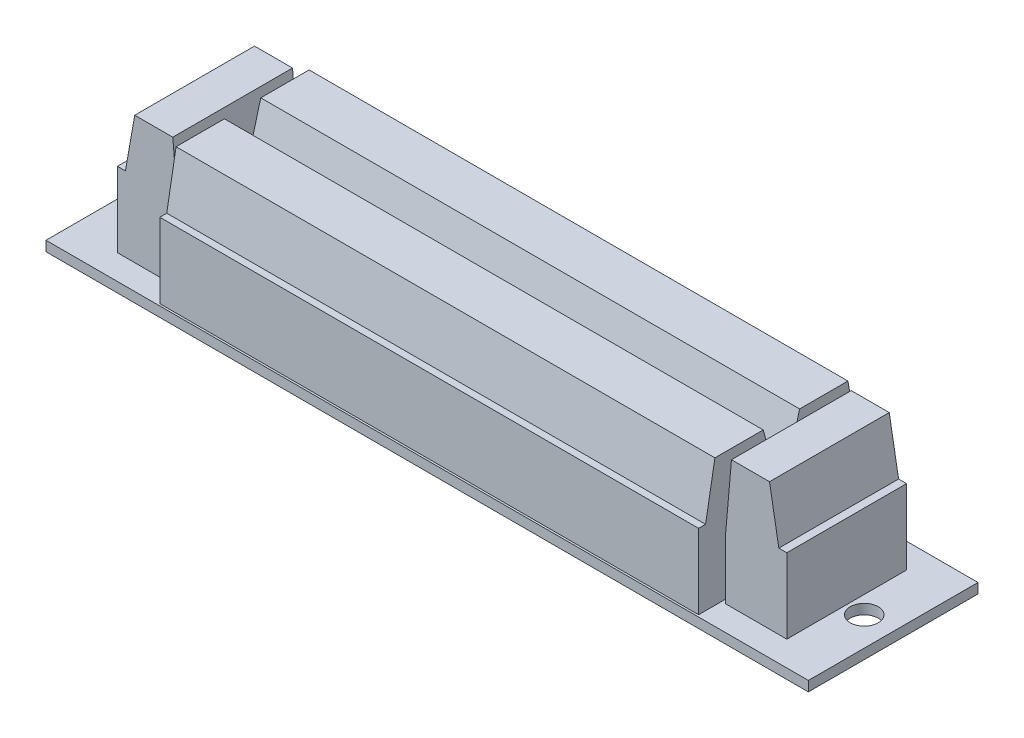
SolidWorks part; units mm, degrees
ref_plane "Front Plane" through (0, 0, 0) normal (0, 0, 1) x (1, 0, 0)
ref_plane "Top Plane" through (0, 0, 0) normal (0, 1, 0) x (1, 0, 0)
ref_plane "Right Plane" through (0, 0, 0) normal (1, 0, 0) x (0, 0, -1)
sketch "Sketch1" plane through (0, 0, 0) normal (0, 1, 0) x (1, 0, 0)
  line L0 (0, 10.795) -> (0, -10.795) construction
  line L1 (-48.514, 10.795) -> (48.514, 10.795)
  line L2 (-48.514, 10.795) -> (-48.514, -10.795)
  line L3 (-48.514, -10.795) -> (48.514, -10.795)
  line L4 (48.514, 10.795) -> (48.514, -10.795)
  line L5 (-48.514, 10.795) -> (48.514, -10.795) construction
  line L6 (-48.514, -10.795) -> (48.514, 10.795) construction
  circle A0 centre (-44.831, 0) radius 1.778
  circle A1 centre (44.831, 0) radius 1.778
  point P0 (0, 0)
  dimension "D3" = 3.556
  dimension "D1" = 97.028
  dimension "D2" = 21.59
  dimension "D4" = 89.662
extrude "Boss-Extrude1" add sketch "Sketch1" along normal mid plane 1.27
sketch "Sketch2" plane through (0, 0, 0) normal (1, 0, 0) x (0, 0, -1)
  line L0 (-10.541, 0.635) -> (-10.541, 10.16)
  line L1 (-10.541, 10.16) -> (-9.652, 10.16)
  line L2 (-9.652, 10.16) -> (-8.4651, 16.891)
  line L3 (-8.4651, 16.891) -> (-2.314, 16.891)
  line L4 (-2.314, 16.891) -> (0, 8.255)
  line L5 (0, 8.255) -> (0, 0.635) construction
  line L6 (-10.795, 0.635) -> (10.795, 0.635) construction
  line L7 (10.541, 0.635) -> (-10.541, 0.635)
  line L8 (10.541, 0.635) -> (10.541, 10.16)
  line L9 (10.541, 10.16) -> (9.652, 10.16)
  line L10 (9.652, 10.16) -> (8.4651, 16.891)
  line L11 (8.4651, 16.891) -> (2.314, 16.891)
  line L12 (2.314, 16.891) -> (0, 8.255)
  point P10 (-10.0965, 10.16)
  point P14 (10.0965, 10.16)
  dimension "D1" = 9.525
  dimension "D2" = 0.889
  dimension "D3" = 16.256
  dimension "D4" = 100
  dimension "D5" = 7.62
  dimension "D6" = 30
  dimension "D7" = 0.254
extrude "Boss-Extrude2" add sketch "Sketch2" along normal mid plane 68.58
sketch "Sketch3" plane through (0, 0, 0) normal (0, 0, 1) x (1, 0, 0)
  line L0 (-34.798, 0.635) -> (-34.798, 8.255)
  line L1 (-48.514, 0.635) -> (48.514, 0.635) construction
  line L2 (-34.798, 8.255) -> (-35.5536, 16.891)
  line L3 (-35.5536, 16.891) -> (-40.3936, 16.891)
  line L4 (-40.3936, 16.891) -> (-41.5804, 10.16)
  line L5 (-41.5804, 10.16) -> (-42.5964, 10.16)
  line L6 (-42.5964, 10.16) -> (-42.5964, 0.635)
  line L7 (-42.5964, 0.635) -> (-34.798, 0.635)
  line L8 (-34.29, 10.16) -> (-34.29, 0.635) construction
  dimension "D1" = 5
  dimension "D2" = 0.508
  dimension "D3" = 100
  dimension "D4" = 1.016
  dimension "D5" = 9.525
  dimension "D6" = 7.7984
  dimension "D7" = 16.256
  dimension "D8" = 7.62
extrude "Boss-Extrude3" add sketch "Sketch3" along normal mid plane 15.24
mirror "Mirror1" about plane through (0, 0, 0) normal (1, 0, 0) of "Boss-Extrude3"
